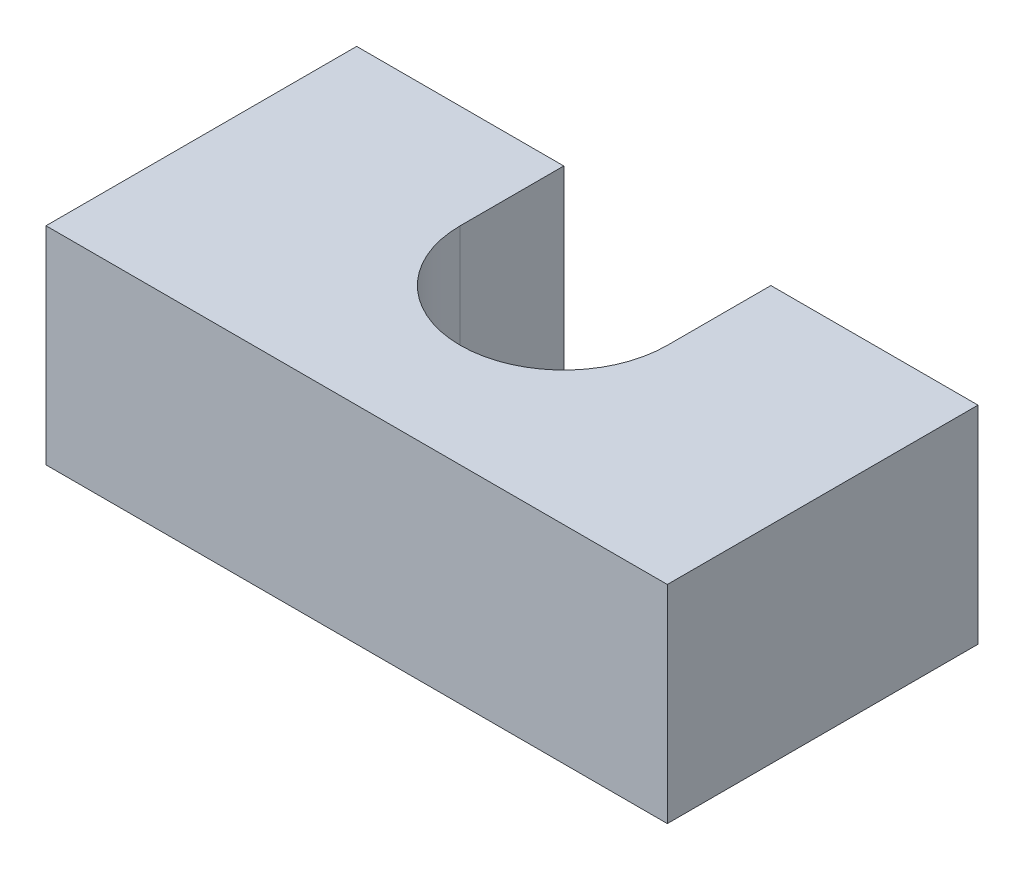
SolidWorks part; units mm, degrees
ref_plane "Přední rovina" through (0, 0, 0) normal (0, 0, 1) x (1, 0, 0)
ref_plane "Horní rovina" through (0, 0, 0) normal (0, 1, 0) x (1, 0, 0)
ref_plane "Pravá rovina" through (0, 0, 0) normal (1, 0, 0) x (0, 0, -1)
sketch "Sketch2" plane through (0, 0, 0) normal (0, 1, 0) x (1, 0, 0)
  line L0 (-10, 0) -> (-10, -10)
  line L3 (30, -30) -> (-30, -30)
  line L4 (-30, -30) -> (-30, 0)
  line L5 (-30, 0) -> (-10, 0)
  line L6 (0, 0) -> (0, -30) construction
  line L7 (30, 0) -> (10, 0)
  line L8 (30, -30) -> (30, 0)
  line L9 (10, 0) -> (10, -10)
  arc A0 (-10, -10) -> (10, -10) centre (0, -10) ccw
  point P4 (-30, -31.1559)
  dimension "D2" = 10
  dimension "D1" = 20
  dimension "D3" = 30
  dimension "D4" = 10
extrude "Boss-Extrude1" add sketch "Sketch2" along normal blind 20
equation "\"R\"= 10"
equation "\"D2@Sketch2\"=\"R\""
equation "\"D1@Sketch2\"=\"R\" *2"
equation "\"D3@Sketch2\"=\"R\"*3"
equation "\"D4@Sketch2\"=\"R\""
